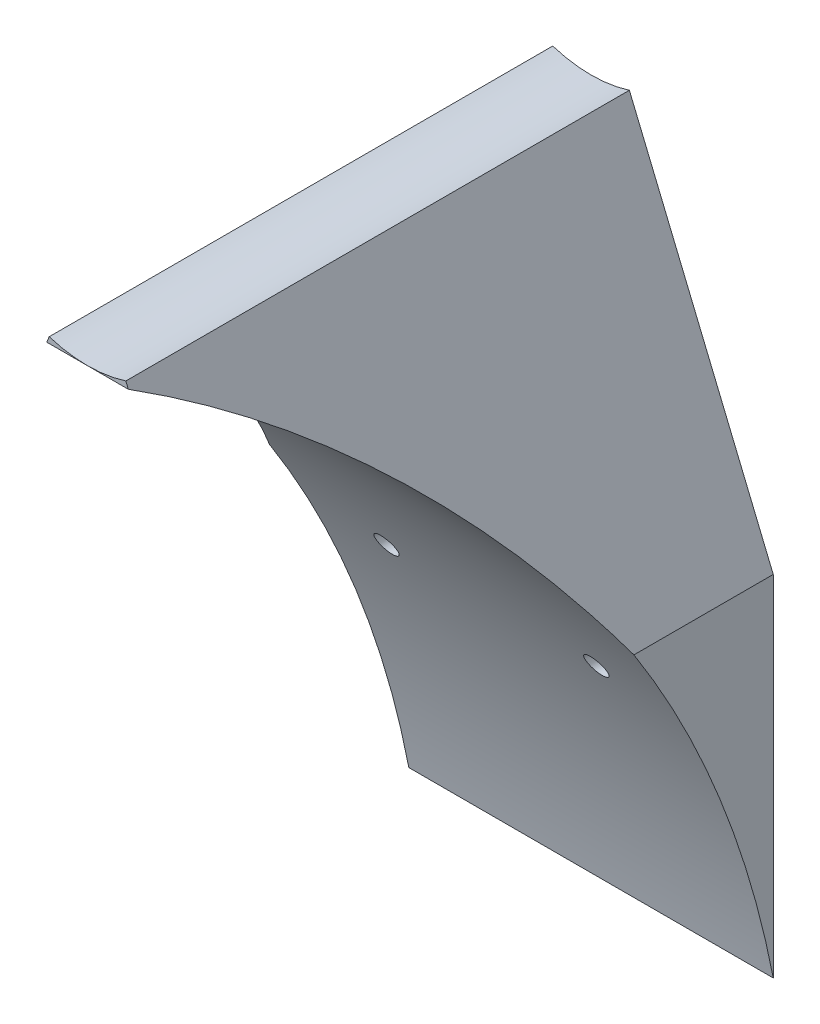
SolidWorks part; units mm, degrees
ref_plane "Front Plane" through (0, 0, 0) normal (0, 0, 1) x (1, 0, 0)
ref_plane "Top Plane" through (0, 0, 0) normal (0, 1, 0) x (1, 0, 0)
ref_plane "Right Plane" through (0, 0, 0) normal (1, 0, 0) x (0, 0, -1)
sketch "Sketch1" plane through (0, 0, 0) normal (0, 0, 1) x (1, 0, 0)
  line L0 (0, 0) -> (0, -127) construction
  line L1 (0, 0) -> (29.1605, -70.3996) construction
  line L2 (0, 0) -> (-29.1605, -70.3996) construction
  line L3 (-29.1605, -70.3996) -> (-29.1605, -123.6069) construction
  line L5 (0, 0) -> (0, -127) construction
  line L6 (29.1605, -123.6069) -> (29.1605, -70.3996) construction
  line L7 (29.1605, -123.6069) -> (29.1605, -161.7069) construction
  line L8 (-50.8, -190.8674) -> (0, -190.8674) construction
  line L9 (-50.8, -189.2799) -> (0, -189.2799) construction
  line L10 (27.573, -123.6069) -> (27.573, -161.7069) construction
  line L11 (27.573, -123.6069) -> (27.573, -70.7154)
  line L12 (0, -4.1483) -> (27.573, -70.7154)
  line L13 (0, -4.1483) -> (-27.573, -70.7154)
  line L14 (-27.573, -70.7154) -> (-27.573, -123.6069)
  line L15 (-27.573, -123.6069) -> (-29.1605, -123.6069) construction
  line L16 (-50.8, -189.2799) -> (-50.8, -190.8674) construction
  line L17 (27.573, -123.6069) -> (-27.573, -123.6069)
  circle A0 centre (0, 0) radius 127 construction
  circle A1 centre (0, 0) radius 76.2 construction
  arc A2 (29.1605, -161.7069) -> (0, -190.8674) centre (0, -161.7069) cw construction
  arc A3 (27.573, -161.7069) -> (0, -189.2799) centre (0, -161.7069) cw construction
  point P2 (-15.875, -74.528)
  point P12 (0, 0)
  point P14 (15.875, -74.528)
  point P25 (0, -38.1)
  dimension "D2" = 152.4
  dimension "D6" = 1.5875
  dimension "D1" = 127
  dimension "D3" = 38.1
  dimension "D4" = 50.8
  dimension "D5" = 45
  dimension "D7" = 38.1
  dimension "D8" = 31.75
extrude "Boss-Extrude1" add sketch "Sketch1" along normal blind 76.2
sketch "Sketch2" plane through (0, 0, 0) normal (1, 0, 0) x (0, 0, -1)
  line L3 (-76.2, -123.6069) -> (0, -123.6069) construction
  line L4 (-76.2, -123.6069) -> (-76.2, -70.7154) construction
  line L5 (-76.2, -70.7154) -> (-76.2, -4.1483) construction
  line L6 (-76.2, -123.6069) -> (0, -123.6069)
  line L7 (-76.2, -123.6069) -> (-76.2, -70.7154)
  line L8 (-76.2, -70.7154) -> (-76.2, -19.05)
  arc A0 (-76.2, -19.05) -> (0, -123.6069) centre (-149.6166, -152.6006) cw
  dimension "D1" = 19.05
  dimension "D2" = 152.4
extrude "Cut-Extrude1" cut sketch "Sketch2" along normal up to surface (55.146 mm away) from surface
sketch "Sketch5" plane through (0, 0, 0) normal (0, 0, 1) x (1, 0, 0)
  line L0 (0, -82.55) -> (0, 0) construction
  circle A0 centre (0, 0) radius 82.55 construction
  point P0 (0, -38.1)
  point P4 (-15.875, -81.0092)
  point P5 (15.875, -81.0092)
  dimension "D1" = 38.1
  dimension "D3" = 165.1
  dimension "D2" = 31.75
hole_wizard "M3 Clearance Hole1" positions "Sketch7" profile "Sketch8" hole size "M3" standard "ANSI Metric" end condition through all
sketch "Sketch7" plane through (0, 0, 0) normal (0, 0, -1) x (-1, 0, 0)
  point P0 (-15.875, -81.0092)
  point P3 (15.875, -81.0092)
  point P6 (0, -38.1)
sketch "Sketch8" plane through (15.875, -81.0092, 0) normal (1, 0, 0) x (0, 1, 0)
  line L0 (0, 0) -> (0, 76.2)
  line L1 (0, 76.2) -> (1.7, 76.2)
  line L2 (1.7, 76.2) -> (1.7, 0)
  line L5 (1.7, 0) -> (0, 0)
  line L11 (0, -6.35) -> (0, 107.95) construction
  dimension "Thru Hole Dia." = 3.4
  dimension "Thru Hole Depth" = 76.2
sketch "Sketch10" plane through (0, 0, 0) normal (0, 0, -1) x (-1, 0, 0)
  circle A0 centre (0, 0) radius 19.05
  dimension "D1" = 38.1
extrude "Cut-Extrude2" cut sketch "Sketch10" against normal up to next
